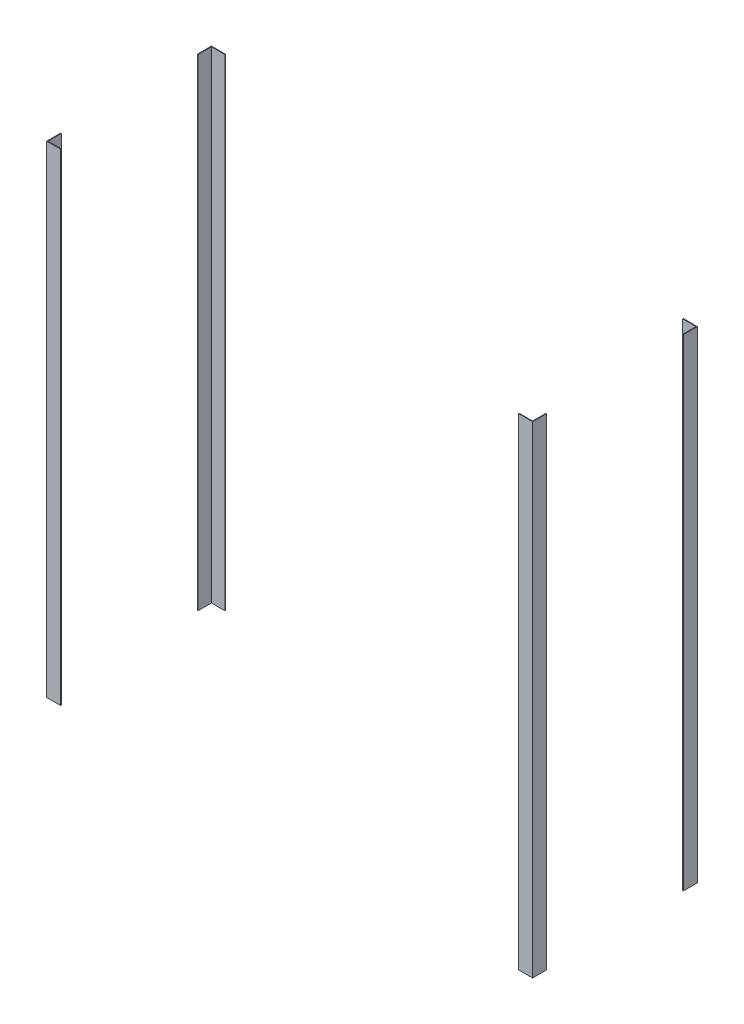
SolidWorks part; units mm, degrees
material "Plain Carbon Steel"
ref_plane "Front Plane" through (0, 0, 0) normal (0, 0, 1) x (1, 0, 0)
ref_plane "Top Plane" through (0, 0, 0) normal (0, 1, 0) x (1, 0, 0)
ref_plane "Right Plane" through (0, 0, 0) normal (1, 0, 0) x (0, 0, -1)
sketch "Sketch1" plane through (0, 0, 0) normal (0, 1, 0) x (1, 0, 0)
  line L1 (-922.3375, -312.7375) -> (-869.1562, -312.7375)
  line L2 (-922.3375, -312.7375) -> (-922.3375, -259.5563)
  line L3 (-922.3375, 312.7375) -> (-869.1562, 312.7375)
  line L4 (922.3375, -312.7375) -> (922.3375, -259.5563)
  line L5 (-922.3375, -312.7375) -> (922.3375, 312.7375) construction
  line L6 (-922.3375, 312.7375) -> (922.3375, -312.7375) construction
  line L10 (-919.9562, -310.3563) -> (-919.9562, -259.5563)
  line L11 (-919.9562, 310.3562) -> (-869.1562, 310.3562)
  line L12 (919.9562, -310.3563) -> (919.9562, -259.5563)
  line L13 (-919.9562, -310.3563) -> (-869.1562, -310.3563)
  line L14 (-869.1562, 312.7375) -> (-869.1562, 310.3562)
  line L15 (869.1562, 312.7375) -> (869.1562, 310.3562)
  line L16 (-922.3375, 259.5562) -> (-919.9562, 259.5562)
  line L17 (-922.3375, -259.5563) -> (-919.9562, -259.5563)
  line L18 (919.9562, 259.5562) -> (922.3375, 259.5562)
  line L19 (919.9562, -259.5563) -> (922.3375, -259.5563)
  line L20 (-869.1562, -310.3563) -> (-869.1562, -312.7375)
  line L21 (869.1562, -310.3563) -> (869.1562, -312.7375)
  line L22 (869.1562, 312.7375) -> (922.3375, 312.7375)
  line L23 (869.1562, 310.3562) -> (919.9562, 310.3562)
  line L24 (-869.1562, 312.7375) -> (869.1562, 312.7375) construction
  line L25 (-922.3375, 312.7375) -> (922.3375, 312.7375) construction
  line L26 (869.1562, -312.7375) -> (922.3375, -312.7375)
  line L27 (-869.1562, 310.3562) -> (869.1562, 310.3562) construction
  line L28 (-919.9562, 310.3562) -> (919.9562, 310.3562) construction
  line L29 (869.1562, -310.3563) -> (919.9562, -310.3563)
  line L30 (-869.1562, -312.7375) -> (869.1562, -312.7375) construction
  line L31 (-922.3375, -312.7375) -> (922.3375, -312.7375) construction
  line L32 (922.3375, 259.5562) -> (922.3375, 312.7375)
  line L33 (-869.1562, -310.3563) -> (869.1562, -310.3563) construction
  line L34 (-919.9562, -310.3563) -> (919.9562, -310.3563) construction
  line L35 (919.9562, 259.5562) -> (919.9562, 310.3562)
  line L36 (922.3375, -259.5563) -> (922.3375, 259.5562) construction
  line L37 (922.3375, -312.7375) -> (922.3375, 312.7375) construction
  line L38 (-922.3375, 259.5562) -> (-922.3375, 312.7375)
  line L39 (919.9562, -259.5563) -> (919.9562, 259.5562) construction
  line L40 (919.9562, -310.3563) -> (919.9562, 310.3562) construction
  line L41 (-919.9562, 259.5562) -> (-919.9562, 310.3562)
  line L42 (-922.3375, -259.5563) -> (-922.3375, 259.5562) construction
  line L43 (-922.3375, -312.7375) -> (-922.3375, 312.7375) construction
  line L45 (-919.9562, -259.5563) -> (-919.9562, 259.5562) construction
  line L46 (-919.9562, -310.3563) -> (-919.9562, 310.3562) construction
  point P0 (0, 0)
  dimension "D1" = 1844.675
  dimension "D2" = 625.475
  dimension "D4" = 50.8
  dimension "D5" = 53.1812
  dimension "D3" = 2.3813
extrude "Boss-Extrude1" add sketch "Sketch1" along normal blind 1828.8
